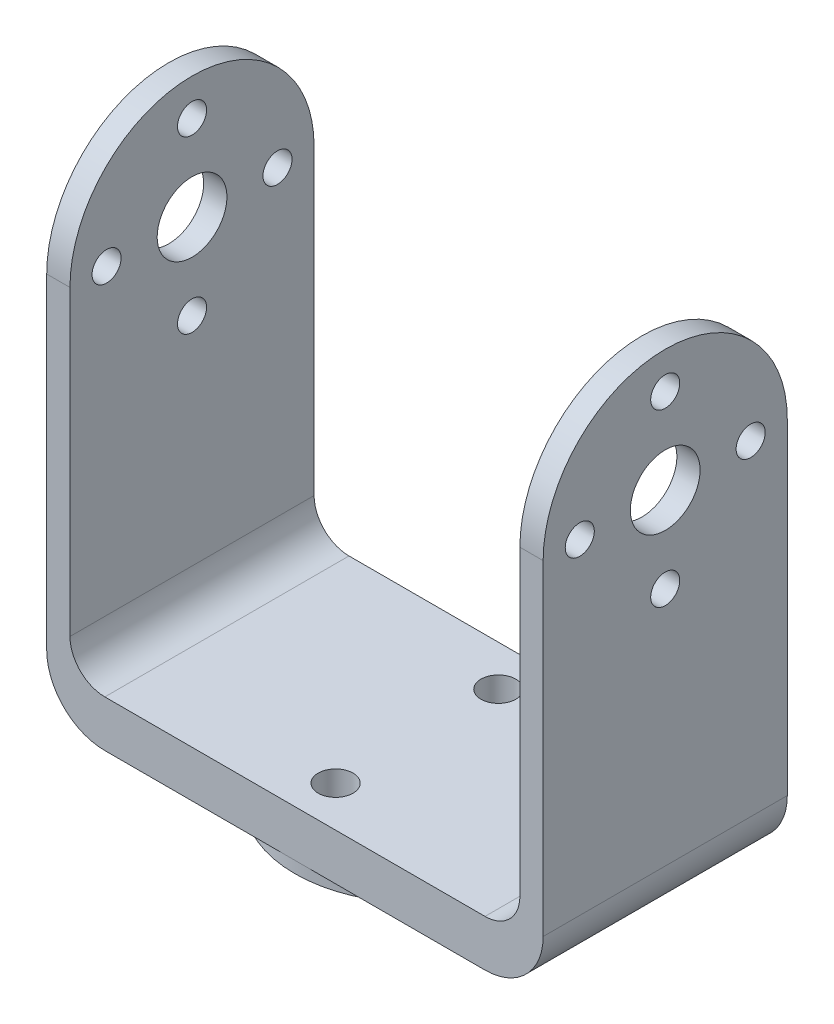
SolidWorks part; units mm, degrees
ref_plane "前视基准面" through (0, 0, 0) normal (0, 0, 1) x (1, 0, 0)
ref_plane "上视基准面" through (0, 0, 0) normal (0, 1, 0) x (1, 0, 0)
ref_plane "右视基准面" through (0, 0, 0) normal (1, 0, 0) x (0, 0, -1)
other "Configuration Table"
sketch "草图1" plane through (0, 0, 0) normal (0, 1, 0) x (1, 0, 0)
  line L0 (0, 10.5) -> (0, -10.5) construction
  line L1 (-21.35, 10.5) -> (21.35, 10.5)
  line L2 (-21.35, 10.5) -> (-21.35, -10.5)
  line L3 (-21.35, -10.5) -> (21.35, -10.5)
  line L4 (21.35, 10.5) -> (21.35, -10.5)
  line L5 (-21.35, 10.5) -> (21.35, -10.5) construction
  line L6 (-21.35, -10.5) -> (21.35, 10.5) construction
  line L7 (-21.35, 0) -> (21.35, 0) construction
  line L8 (8.018, 1.5509) -> (12.9126, 1.5509)
  line L9 (8.018, -1.5509) -> (12.9126, -1.5509)
  line L10 (-8.018, -1.5509) -> (-12.9126, -1.5509)
  line L11 (-8.018, 1.5509) -> (-12.9126, 1.5509)
  circle A0 centre (7.5, 5) radius 1.5
  arc A1 (12.9126, 1.5509) -> (14.6975, 0) centre (13.0296, -0.117) cw
  arc A2 (12.9126, -1.5509) -> (14.6975, 0) centre (13.0296, 0.117) ccw
  circle A3 centre (7.5, -5) radius 1.5
  circle A4 centre (-7.5, -5) radius 1.5
  arc A5 (-12.9126, -1.5509) -> (-14.6975, 0) centre (-13.0296, 0.117) cw
  arc A6 (-12.9126, 1.5509) -> (-14.6975, 0) centre (-13.0296, -0.117) ccw
  circle A7 centre (-7.5, 5) radius 1.5
  spline S0 degree 3 poles (0, 7.4073) (2.0925, 7.358) (3.0437, 2.9519) (6.0077, 1.6267) (8.018, 1.5509) knots 0 0 0 0 0.496823 1 1 1 1
  spline S1 degree 3 poles (0, -7.4073) (2.0925, -7.358) (3.0437, -2.9519) (6.0077, -1.6267) (8.018, -1.5509) knots 0 0 0 0 0.496823 1 1 1 1
  spline S2 degree 3 poles (0, -7.4073) (-2.0925, -7.358) (-3.0437, -2.9519) (-6.0077, -1.6267) (-8.018, -1.5509) knots 0 0 0 0 0.496823 1 1 1 1
  spline S3 degree 3 poles (0, 7.4073) (-2.0925, 7.358) (-3.0437, 2.9519) (-6.0077, 1.6267) (-8.018, 1.5509) knots 0 0 0 0 0.496823 1 1 1 1
  point P0 (0, 0)
  point P6 (7.5, 5)
  point P13 (0, 7.4073)
  point P14 (2.4183, 5.7294)
  point P15 (3.5345, 3.7404)
  point P16 (4.8936, 2.4067)
  point P17 (8.018, 1.5509)
  dimension "D5" = 3
  dimension "D1" = 21
  dimension "D2" = 42.7
  dimension "D3" = 7.5
  dimension "D4" = 5
extrude "凸台-拉伸1" add sketch "草图1" along normal blind 2
sketch "草图2" plane through (-21.35, 0, 0) normal (-1, 0, 0) x (0, 0, 1)
  line L0 (-10.5, 2) -> (-10.5, 32)
  line L1 (10.5, 2) -> (10.5, 32)
  line L2 (-10.5, 32) -> (10.5, 32) construction
  line L3 (0, 32) -> (0, 42.5) construction
  line L4 (-10.5, 2) -> (10.5, 2)
  line L5 (0, 32) -> (0, 24.65) construction
  line L7 (0, 20.3593) -> (0, 5.6575) construction
  arc A0 (-10.5, 32) -> (10.5, 32) centre (0, 32) cw
  circle A1 centre (0, 24.65) radius 1.25
  circle A2 centre (-7.35, 32) radius 1.25
  circle A3 centre (0, 39.35) radius 1.25
  circle A4 centre (7.35, 32) radius 1.25
  circle A5 centre (0, 32) radius 3
  point P12 (-7.35, 32)
  point P13 (7.35, 32)
  point P14 (0, 39.35)
  point P24 (0, 21.201)
  point P29 (-1.6717, 25.2356)
  point P34 (0, 0)
  dimension "D5" = 2.5
  dimension "D9" = 2.5
  dimension "D10" = 2.5
  dimension "D11" = 2.5
  dimension "D12" = 6
  dimension "D1" = 30
  dimension "D2" = 30
  dimension "D3" = 10.5
  dimension "D4" = 7.35
  dimension "D6" = 7.35
  dimension "D7" = 7.35
  dimension "D8" = 7.35
extrude "凸台-拉伸2" add sketch "草图2" against normal blind 2
mirror "镜向1" about plane through (0, 0, 0) normal (1, 0, 0) of "凸台-拉伸2"
sketch "草图3" plane through (0, 0, 0) normal (0, -1, 0) x (1, 0, 0)
  line L1 (-21.35, 10.5) -> (21.35, 10.5)
  line L2 (-21.35, 10.5) -> (-21.35, -10.5)
  line L3 (-21.35, -10.5) -> (21.35, -10.5)
  line L4 (21.35, 10.5) -> (21.35, -10.5)
extrude "凸台-拉伸3" add sketch "草图3" along normal blind 1 and the other way blind 3
sketch "草图4" plane through (0, -1, 0) normal (0, -1, 0) x (1, 0, 0)
  line L0 (-21.35, 10.5) -> (21.35, -10.5) construction
  line L1 (21.35, 10.5) -> (-21.35, -10.5) construction
  line L2 (0, 0) -> (0, 7) construction
  line L3 (0, 0) -> (0, -7) construction
  circle A0 centre (0, 7) radius 1.5
  circle A1 centre (0, -7) radius 1.5
  circle A2 centre (0, 0) radius 10.5
  dimension "D3" = 3
  dimension "D4" = 3
  dimension "D1" = 7
  dimension "D2" = 7
extrude "凸台-拉伸4" add sketch "草图4" along normal blind 1
fillet "圆角1" radius 3 2 edges at (19.35, 3, 0) (-19.35, 3, 0)
fillet "圆角2" radius 5 2 edges at (21.35, -1, 0) (-21.35, -1, 0)
sketch "草图6" plane through (0, -1, 0) normal (0, -1, 0) x (1, 0, 0)
  circle A0 centre (0, 7) radius 1.5
  circle A1 centre (0, -7) radius 1.5
extrude "切除-拉伸1" cut sketch "草图6" against normal up to surface (4 mm away) up to face at (0, 3, 0)
